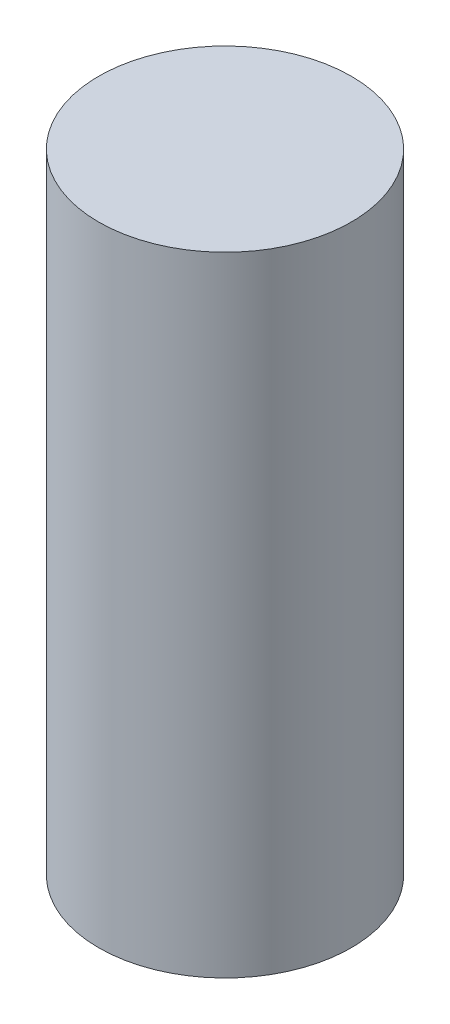
SolidWorks part; units mm, degrees
material "Alloy Steel"
ref_plane "Front Plane" through (0, 0, 0) normal (0, 0, 1) x (1, 0, 0)
ref_plane "Top Plane" through (0, 0, 0) normal (0, 1, 0) x (1, 0, 0)
ref_plane "Right Plane" through (0, 0, 0) normal (1, 0, 0) x (0, 0, -1)
sketch "Sketch1" plane through (0, 0, 0) normal (0, 1, 0) x (1, 0, 0)
  circle A0 centre (0, 0) radius 2.5527
  dimension "D1" = 5.1054
extrude "Boss-Extrude1" add sketch "Sketch1" along normal blind 12.7
